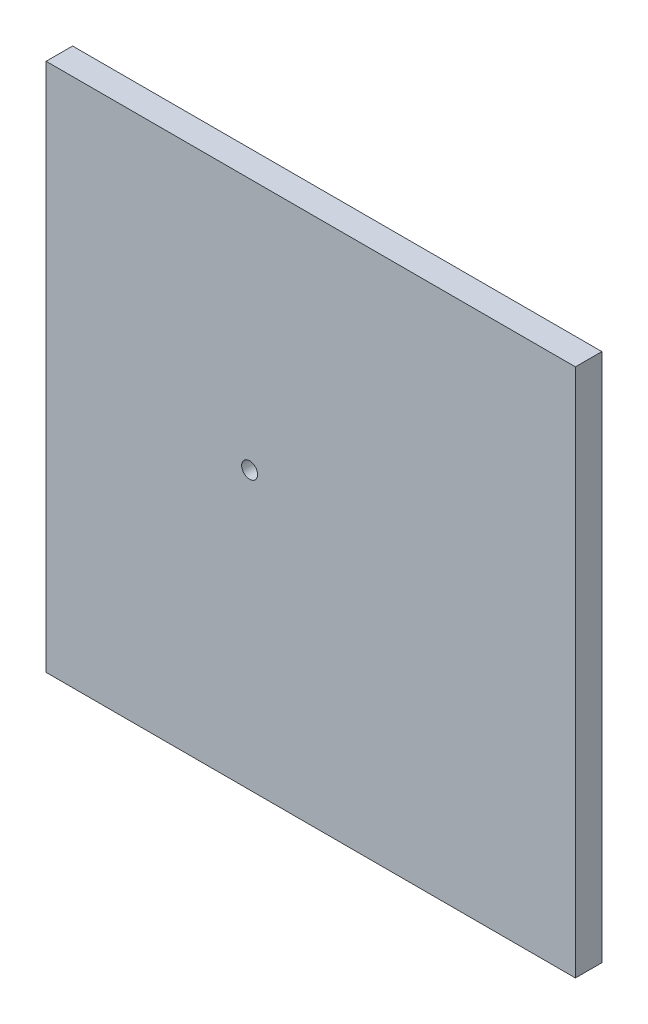
SolidWorks part; units mm, degrees
ref_plane "Front Plane" through (0, 0, 0) normal (0, 0, 1) x (1, 0, 0)
ref_plane "Top Plane" through (0, 0, 0) normal (0, 1, 0) x (1, 0, 0)
ref_plane "Right Plane" through (0, 0, 0) normal (1, 0, 0) x (0, 0, -1)
sketch "Sketch1" plane through (0, 0, 0) normal (0, 0, 1) x (1, 0, 0)
  line L1 (-127, -127) -> (127, -127)
  line L2 (-127, -127) -> (-127, 127)
  line L3 (-127, 127) -> (127, 127)
  line L4 (127, -127) -> (127, 127)
  line L5 (-127, -127) -> (127, 127) construction
  line L6 (-127, 127) -> (127, -127) construction
  point P0 (0, 0)
  dimension "D1" = 254
  dimension "D2" = 254
extrude "Boss-Extrude1" add sketch "Sketch1" along normal blind 12.7
sketch "Sketch2" plane through (0, 0, 12.7) normal (0, 0, 1) x (1, 0, 0)
  circle A0 centre (-29.3428, 5.9536) radius 3.8273
extrude "Cut-Extrude1" cut sketch "Sketch2" against normal through all
